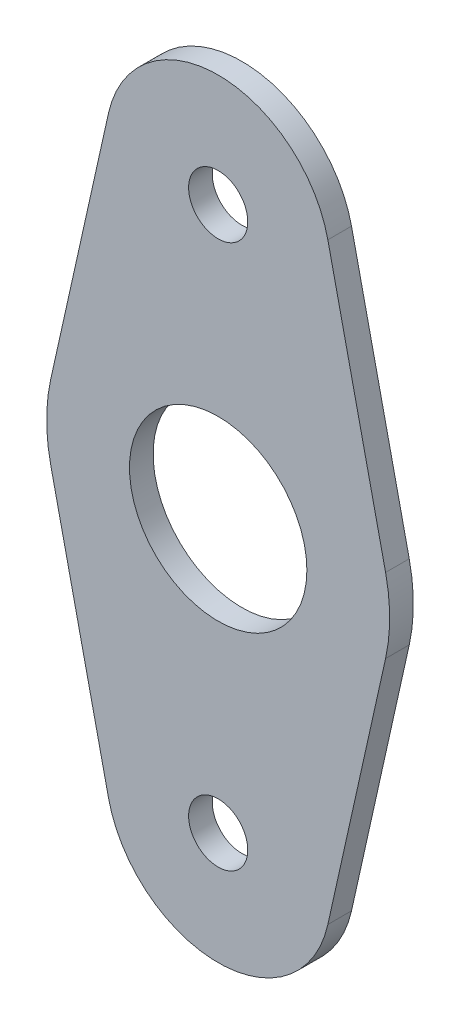
SolidWorks part; units mm, degrees
material "6061-T6 (SS)"
ref_plane "Front Plane" through (0, 0, 0) normal (0, 0, 1) x (1, 0, 0)
ref_plane "Top Plane" through (0, 0, 0) normal (0, 1, 0) x (1, 0, 0)
ref_plane "Right Plane" through (0, 0, 0) normal (1, 0, 0) x (0, 0, -1)
sketch "Sketch1" plane through (0, 0, 0) normal (0, 0, 1) x (1, 0, 0)
  line L0 (0, 0) -> (7.5, 0) construction
  line L1 (-9.2728, 25.0652) -> (-14.1532, 3.1522)
  line L2 (9.2728, 25.0652) -> (14.1532, 3.1522)
  line L3 (9.2728, -25.0652) -> (14.1532, -3.1522)
  line L4 (-9.2728, -25.0652) -> (-14.1532, -3.1522)
  circle A0 centre (0, 0) radius 7.5
  circle A1 centre (0, 23) radius 2.5
  arc A2 (9.2728, 25.0652) -> (-9.2728, 25.0652) centre (0, 23) ccw
  arc A3 (-14.1532, 3.1522) -> (-14.1532, -3.1522) centre (0, 0) ccw
  circle A4 centre (0, -23) radius 2.5
  arc A5 (-9.2728, 25.0652) -> (9.2728, 25.0652) centre (0, 23) ccw construction
  circle A6 centre (0, 23) radius 9.5 construction
  arc A7 (14.1532, 3.1522) -> (-14.1532, 3.1522) centre (0, 0) ccw construction
  circle A8 centre (0, 0) radius 14.5 construction
  arc A9 (9.2728, -25.0652) -> (-9.2728, -25.0652) centre (0, -23) cw
  arc A10 (14.1532, -3.1522) -> (14.1532, 3.1522) centre (0, 0) ccw
  arc A11 (-14.1532, -3.1522) -> (14.1532, -3.1522) centre (0, 0) ccw construction
  point P7 (10.5, 0)
  point P14 (10.2489, 2.2826)
  point P15 (5.5, 23)
  dimension "D1" = 15
  dimension "D2" = 5
  dimension "D3" = 23
  dimension "D4" = 7
extrude "Boss-Extrude1" add sketch "Sketch1" along normal mid plane 2
